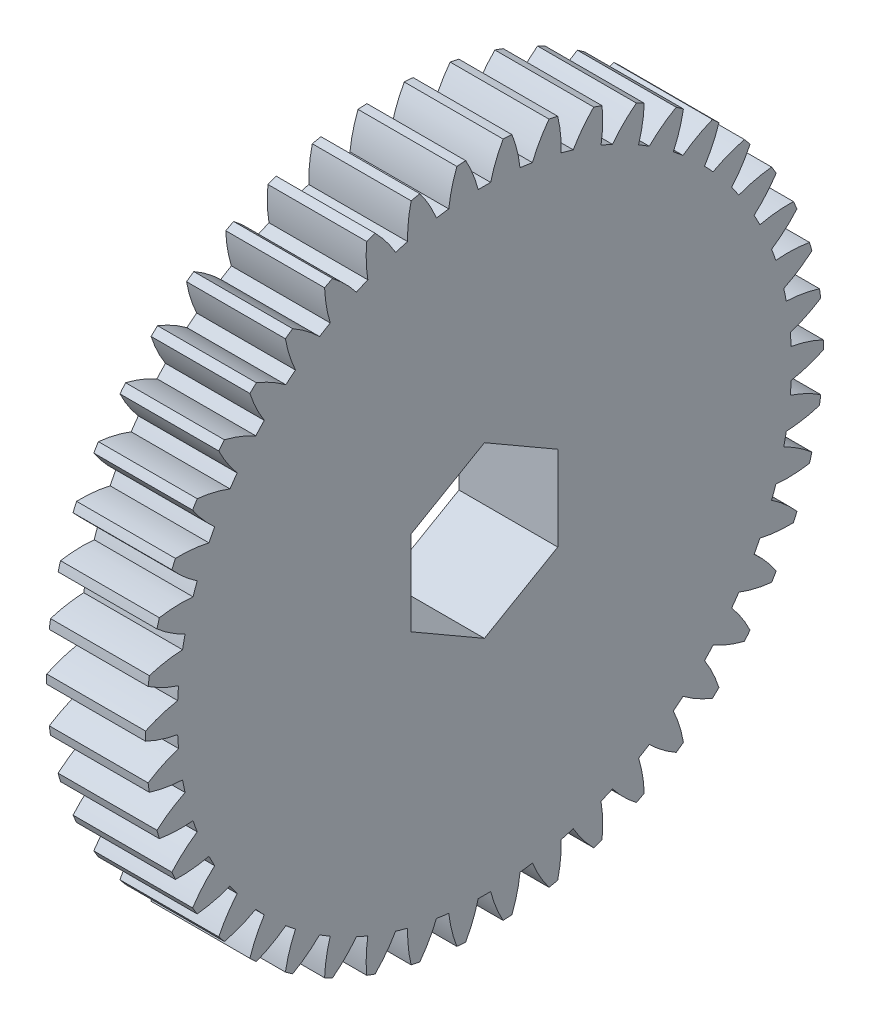
SolidWorks part; units mm, degrees
material "AISI 4340 Aço, normalizado"
ref_plane "Plane1" through (0, 0, 0) normal (0, 0, 1) x (1, 0, 0)
ref_plane "Plane2" through (0, 0, 0) normal (0, 1, 0) x (1, 0, 0)
ref_plane "Plane3" through (0, 0, 0) normal (1, 0, 0) x (0, 0, -1)
sketch "HoldingSke" plane through (0, 0, 0) normal (0, 1, 0) x (1, 0, 0)
  line L0 (0, 0) -> (0.6947, -0.7193)
  line L1 (-15, 0) -> (100, 0) construction
  line L2 (0, 0) -> (-2.1039, 2.3779)
  line L3 (0, 0) -> (-11.863, 4.5341)
  line L4 (0, 0) -> (5.9991, 6.2122)
  line L5 (0, 0) -> (-46.8476, -17.4728)
  line L6 (0, 0) -> (-8.2896, -5.593)
  line L7 (-2.1039, 2.3779) -> (8.6586, 51.2059)
  line L8 (-76.2, 54.61) -> (-74.4, 54.61)
  line L9 (-71.009, 38.7566) -> (-53.1078, 45.2721)
  line L10 (-76.2, 71.12) -> (104.1128, 71.12)
  line L11 (0, 0) -> (-10, 0)
  line L12 (-76.2, 101.6) -> (-76.162, 101.6)
  line L13 (24.9733, 27.94) -> (52.9518, 28.4284)
  line L14 (24.9733, 27.94) -> (24.9743, 27.94)
  line L15 (24.9733, 27.94) -> (100.4006, 29.5858)
  line L16 (-63.627, -1) -> (-12.827, -1)
  circle A0 centre (0, 0) radius 5
  circle A1 centre (0, 0) radius 21.749
  circle A2 centre (0, 0) radius 37.5
  circle A3 centre (0, 0) radius 5
  dimension "MHD" = 43.498
  dimension "Hub_dia" = 75
  dimension "Bore" = 10
  dimension "MBD" = 10
  dimension "Num_teeth" = 46
  dimension "Pitch" = 1
  dimension "Overall_len" = 50
  dimension "Show_teeth" = 46
  dimension "Thickness" = 10
  dimension "OAL" = 50.0001
  dimension "T_dim" = 1.8
  dimension "Ap" = 20
  dimension "H" = 19.05
  dimension "Pitch_radius" = 180.3128
  dimension "Width" = 10
  dimension "Backlash" = 0.038
  dimension "Addendum_fac" = 1
  dimension "Dedendum_fac" = 1.25
  dimension "Clearance_fac" = 0.25
  dimension "Dedendum_add" = 0.001
  dimension "Module" = 1
sketch "BasProSke" plane through (0, 0, 0) normal (0, 1, 0) x (1, 0, 0)
  line L0 (-10, 0) -> (60, 0) construction
  line L1 (0, 0) -> (0, 24)
  line L2 (0, 0) -> (10, 0)
  line L3 (10, 0) -> (10, 24)
  line L4 (10, 24) -> (0, 24)
  dimension "Thickness" = 10
  dimension "Diameter" = 48
revolve "Base-Revolve" add sketch "BasProSke" angle 360 about L0
sketch "TooCutSke" plane through (0, 0, 0) normal (1, 0, 0) x (0, 0, -1)
  line L1 (0, 0) -> (0, 107) construction
  line L2 (0, 0) -> (-0.8517, 22.9842) construction
  line L3 (0, 0) -> (-3.1376, 45.8703) construction
  line L4 (-0.8517, 22.9842) -> (-1.5688, 22.9352) construction
  arc A0 (0.4415, 21.7445) -> (-0.4415, 21.7445) centre (0, 0) ccw
  arc A1 (1.3382, 23.9881) -> (-1.3382, 23.9881) centre (0, 0) ccw
  circle A2 centre (0, 0) radius 23 construction
  circle A3 centre (0, 0) radius 21.6129 construction
  arc A4 (-0.4415, 21.7445) -> (-1.3382, 23.9881) centre (-9.3589, 19.4815) ccw
  arc A5 (1.3382, 23.9881) -> (0.4415, 21.7445) centre (9.3589, 19.4815) ccw
  dimension "Root_dia" = 43.498
  dimension "Overcut_dia" = 48.0508
  dimension "Pitch_dia" = 46
  dimension "Base_dia" = 43.2259
  dimension "Flank_rad" = 9.2
  dimension "Half_ang" = 3.913
  dimension "Half_CT" = 0.7187
extrude "ToothCut" cut sketch "TooCutSke" along normal through all
fillet "Breaks" [suppressed] radius 0.02
fillet "RootFillets" [suppressed] radius 0.251
pattern_circular "TeethCuts" count 46 every 7.826 about axis through (-10, 0, 0) along (1, 0, 0) of "ToothCut", "RootFillets", "Breaks"
sketch "HubNeaOneSke" plane through (0, 0, 0) normal (-1, 0, 0) x (0, 0, 1)
  circle A0 centre (0, 0) radius 21.749
  dimension "Diameter" = 43.498
extrude "HubNearOne" [suppressed] add sketch "HubNeaOneSke" along normal blind 40.0001
sketch "HubNeaBotSke" plane through (0, 0, 0) normal (-1, 0, 0) x (0, 0, 1)
  circle A0 centre (0, 0) radius 21.749
  dimension "Diameter" = 43.498
extrude "HubNearBoth" [suppressed] add sketch "HubNeaBotSke" along normal blind 20
ref_plane "FarPln" through (10, 0, 0) normal (1, 0, 0) x (0, 0, -1)
sketch "HubFarSke" plane through (10, 0, 0) normal (1, 0, 0) x (0, 0, -1)
  circle A0 centre (0, 0) radius 21.749
  dimension "Diameter" = 43.498
extrude "HubFar" [suppressed] add sketch "HubFarSke" along normal blind 20
sketch "BorSke" plane through (0, 0, 0) normal (1, 0, 0) x (0, 0, -1)
  circle A0 centre (0, 0) radius 5
  dimension "Diameter" = 10
extrude "Bore" cut sketch "BorSke" along normal mid plane 100.0001
sketch "KeySke" plane through (0, 0, 0) normal (1, 0, 0) x (0, 0, -1)
  line L0 (-2, 0) -> (-2, 6.8)
  line L1 (-2, 6.8) -> (2, 6.8)
  line L2 (2, 6.8) -> (2, 0)
  line L3 (0, 0) -> (0, 34) construction
  line L4 (-2, 0) -> (2, 0)
  dimension "Offset" = 6.8
  dimension "Width" = 4
extrude "Keyway" [suppressed] cut sketch "KeySke" along normal mid plane 100.0001
pattern_circular "Keyway2" [suppressed] count 2 every 90 about axis through (-10, 0, 0) along (1, 0, 0)
sketch "Esboço1" plane through (10, 0, 0) normal (1, 0, 0) x (0, 0, -1)
  circle A0 centre (0, 0) radius 26.2038
extrude "Corte-extrusão1" cut sketch "Esboço1" against normal blind 3
sketch "Esboço2" plane through (0, 0, 0) normal (-1, 0, 0) x (0, 0, 1)
  line L0 (0, 6) -> (0, 0) construction
  line L1 (-5.1962, 3) -> (-5.1962, -3)
  line L2 (-5.1962, -3) -> (0, -6)
  line L3 (0, -6) -> (5.1962, -3)
  line L4 (5.1962, -3) -> (5.1962, 3)
  line L5 (5.1962, 3) -> (0, 6)
  line L6 (0, 6) -> (-5.1962, 3)
  line L7 (0, 0) -> (-5, 0) construction
  circle A0 centre (0, 0) radius 5.1962 construction
  circle A1 centre (0, 0) radius 6 construction
  circle A2 centre (0, 0) radius 5 construction
  dimension "D1" = 12
  dimension "D2" = 90
extrude "Corte-extrusão2" cut sketch "Esboço2" against normal through all
equation "' \"Module@HoldingSke\" = 6.35"
equation "' \"Num_teeth@HoldingSke\" = 12"
equation "' \"Ap@HoldingSke\" =  20"
equation "' \"Ap@HoldingSke\" = 20"
equation "' \"Width@HoldingSke\" = 0.5 * 25.4"
equation "' \"Hub_dia@HoldingSke\"= 1 * 25.4"
equation "' \"Hub_dia@HoldingSke\" = 1 * 25.4"
equation "' \"Overall_len@HoldingSke\" = 1.0 * 25.4"
equation "' \"Bore@HoldingSke\" = 0.75 * 25.4"
equation "' \"T_dim@HoldingSke\" = 0.1 * 25.4"
equation "' \"Width@KeySke\" = 0.25 * 25.4"
equation "' \"Show_teeth@HoldingSke\" = 13"
equation "' \"Backlash@HoldingSke\" = 0.009 * 25.4"
equation "' \"Addendum_fac@HoldingSke\" = 1.0"
equation "' \"Dedendum_fac@HoldingSke\" = 1.25"
equation "' \"Dedendum_add@HoldingSke\" = 0.00005 * 25.4"
equation "' \"Clearance_fac@HoldingSke\" = 0.25"
equation "\"Pitch@HoldingSke\" = 1 / \"Module@HoldingSke\""
equation "\"Overcut_dia@TooCutSke\" = (\"Num_teeth@HoldingSke\" + 2 * \"Addendum_fac@HoldingSke\") / \"Pitch@HoldingSke\" + 0.002 * 25.4"
equation "\"Pitch_dia@TooCutSke\" = \"Num_teeth@HoldingSke\" / \"Pitch@HoldingSke\""
equation "\"Base_dia@TooCutSke\" = \"Num_teeth@HoldingSke\" / \"Pitch@HoldingSke\" * cos((\"Ap@HoldingSke\"  * 3.14159265 / 180))"
equation "\"Root_dia@TooCutSke\" = (\"Num_teeth@HoldingSke\" + 2) / \"Pitch@HoldingSke\" - 2 * (\"Addendum_fac@HoldingSke\" + \"Dedendum_fac@HoldingSke\") / \"Pitch@HoldingSke\" - \"Dedendum_add@HoldingSke\" * 2"
equation "\"Half_ang@TooCutSke\" = 180 / \"Num_teeth@HoldingSke\""
equation "\"Half_CT@TooCutSke\" = \"Num_teeth@HoldingSke\" / \"Pitch@HoldingSke\" * sin((3.14159265 / 2 / \"Num_teeth@HoldingSke\")) / 2 - 7 * \"Backlash@HoldingSke\" / 4"
equation "\"Flank_rad@TooCutSke\" = \"Num_teeth@HoldingSke\" / \"Pitch@HoldingSke\" / 5"
equation "\"Radius@RootFillets\" = \"Clearance_fac@HoldingSke\" / \"Pitch@HoldingSke\" + \"Dedendum_add@HoldingSke\""
equation "\"Break_rad@Breaks\" = 0.02 / \"Pitch@HoldingSke\""
equation "\"Thickness@HoldingSke\" = \"Width@HoldingSke\""
equation "\"OAL@HoldingSke\" = \"Thickness@HoldingSke\""
equation "\"MHD@HoldingSke\" = (\"Num_teeth@HoldingSke\" + 2) / \"Pitch@HoldingSke\" - 2 * (\"Addendum_fac@HoldingSke\" + \"Dedendum_fac@HoldingSke\")  / \"Pitch@HoldingSke\" - \"Dedendum_add@HoldingSke\" * 2"
equation "\"MBD@HoldingSke\" = (\"Num_teeth@HoldingSke\" + 2) / \"Pitch@HoldingSke\" - 2 * (\"Addendum_fac@HoldingSke\" + \"Dedendum_fac@HoldingSke\")  / \"Pitch@HoldingSke\" - \"Dedendum_add@HoldingSke\" * 2 - 0.002 * 25.4"
equation "\"MHD@HoldingSke\" = ((sgn( \"MHD@HoldingSke\" - \"Hub_dia@HoldingSke\" )-1)*( \"MHD@HoldingSke\" - \"Hub_dia@HoldingSke\" ))/-2+ \"Hub_dia@HoldingSke\""
equation "\"MBD@HoldingSke\" = ((sgn( \"MBD@HoldingSke\" - \"Bore@HoldingSke\" )-1)*( \"MBD@HoldingSke\" - \"Bore@HoldingSke\" ))/-2+ \"Bore@HoldingSke\""
equation "\"OAL@HoldingSke\" = ((sgn( \"OAL@HoldingSke\" - \"Overall_len@HoldingSke\" )+1)*( \"OAL@HoldingSke\" - \"Overall_len@HoldingSke\" ))/2 + \"Overall_len@HoldingSke\" + 0.000002 * 25.4"
equation "\"Num_teeth@TeethCuts\" = int( \"Show_teeth@HoldingSke\" ) + 1"
equation "\"Num_teeth@TeethCuts\" = ((sgn( \"Num_teeth@TeethCuts\" - \"Num_teeth@HoldingSke\" )-1)*( \"Num_teeth@TeethCuts\" - \"Num_teeth@HoldingSke\" ))/-2+ \"Num_teeth@HoldingSke\""
equation "\"Num_teeth@TeethCuts\" = ((sgn( \"Num_teeth@TeethCuts\" - 2.0)+1)*( \"Num_teeth@TeethCuts\" - 2.0))/2 +2.0"
equation "\"Angle@TeethCuts\" = 360.0 / \"Num_teeth@HoldingSke\""
equation "\"Diameter@BasProSke\" = (\"Num_teeth@HoldingSke\" + 2 * \"Addendum_fac@HoldingSke\") / \"Pitch@HoldingSke\""
equation "\"Thickness@BasProSke\"  = \"Thickness@HoldingSke\""
equation "' \"Fillet_rad@BasProSke\" =  \"Thickness@HoldingSke\" * 0.05"
equation "' \"Fillet_rad@BasProSke\" = \"Thickness@HoldingSke\" * 0.05"
equation "\"MHD@HoldingSke\" = ((sgn( \"MHD@HoldingSke\" - \"Root_dia@TooCutSke\" )-1)*( \"MHD@HoldingSke\" - \"Root_dia@TooCutSke\" ))/-2+ \"Root_dia@TooCutSke\""
equation "\"Diameter@HubNeaOneSke\" = \"MHD@HoldingSke\""
equation "\"Length@HubNearOne\" = \"OAL@HoldingSke\" - \"Thickness@BasProSke\""
equation "\"Diameter@HubNeaBotSke\" = \"MHD@HoldingSke\""
equation "\"Length@HubNearBoth\" = ( \"OAL@HoldingSke\" - \"Thickness@BasProSke\" ) / 2.0"
equation "\"Thickness@FarPln\" = \"Thickness@BasProSke\""
equation "\"Diameter@HubFarSke\" = \"MHD@HoldingSke\""
equation "\"Length@HubFar\" = ( \"OAL@HoldingSke\" - \"Thickness@BasProSke\" ) / 2.0"
equation "\"Diameter@BorSke\" = \"MBD@HoldingSke\""
equation "\"D1@Bore\" = \"OAL@HoldingSke\" * 2.0"
equation "\"D1@Keyway\" = \"OAL@HoldingSke\" * 2.0"
equation "\"Offset@KeySke\" = \"T_dim@HoldingSke\" + \"MBD@HoldingSke\" / 2.0"
